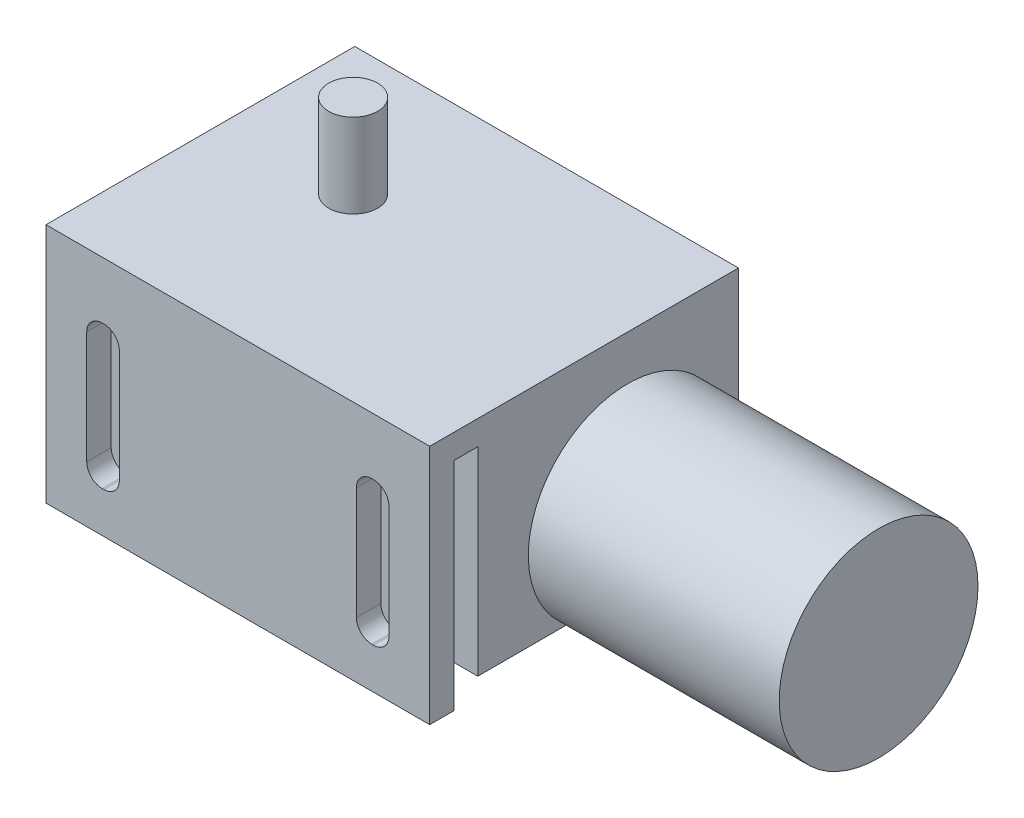
SolidWorks part; units mm, degrees
other "标注1"
sketch "草图20" plane through (-23.55, 25.1, 37.9) normal (-0.2277, 0.5156, 0.826) x (0.9602, 0.2599, 0.1025)
ref_plane "前视基准面" through (0, 0, 0) normal (0, 0, 1) x (1, 0, 0)
ref_plane "上视基准面" through (0, 0, 0) normal (0, 1, 0) x (1, 0, 0)
ref_plane "右视基准面" through (0, 0, 0) normal (1, 0, 0) x (0, 0, -1)
sketch "草图4" plane through (0, 0, 0) normal (0, 0, 1) x (1, 0, 0)
  line L1 (-23.55, 14.8) -> (23.55, 14.8)
  line L2 (-23.55, 14.8) -> (-23.55, -14.8)
  line L3 (-23.55, -14.8) -> (23.55, -14.8)
  line L4 (23.55, 14.8) -> (23.55, -14.8)
  line L5 (-23.55, 14.8) -> (23.55, -14.8) construction
  line L6 (-23.55, -14.8) -> (23.55, 14.8) construction
  point P0 (0, 0)
extrude "减速箱" add sketch "草图4" along normal blind 37.9
sketch "草图8" plane through (0, -14.8, 0) normal (0, -1, 0) x (1, 0, 0)
  line L1 (23.55, 37.9) -> (23.55, 0) construction
  line L2 (-23.55, 0) -> (23.55, 0)
  line L3 (-23.55, 0) -> (-23.55, 32)
  line L4 (-23.55, 32) -> (23.55, 32)
  line L5 (23.55, 0) -> (23.55, 32)
  dimension "D1" = 32
extrude "切除-拉伸1" cut sketch "草图8" against normal blind 2.2
sketch "草图12" plane through (0, -14.8, 0) normal (0, -1, 0) x (1, 0, 0)
  line L0 (23.55, 37.9) -> (23.55, 32) construction
  line L1 (-23.55, 32) -> (23.55, 32)
  line L2 (-23.55, 32) -> (-23.55, 34.9)
  line L3 (-23.55, 34.9) -> (23.55, 34.9)
  line L4 (23.55, 32) -> (23.55, 34.9)
  dimension "D1" = 2.9
extrude "固定凹槽" cut sketch "草图12" against normal offset from surface (26.6 mm away) 3 up to face at (0, 14.8, 18.95)
sketch "草图14" plane through (0, 0, 37.9) normal (0, 0, 1) x (1, 0, 0)
  line L0 (-23.55, 14.8) -> (-23.55, -14.8) construction
  line L3 (-23.55, -14.8) -> (23.55, -14.8) construction
  line L5 (23.55, 14.8) -> (-23.55, 14.8) construction
  line L9 (-14.55, 7.8) -> (-16.65, 7.8)
  line L10 (-14.55, 5.9) -> (-14.55, -7.9)
  line L11 (-16.45, -9.8) -> (-18.55, -9.8)
  line L12 (-18.55, 5.9) -> (-18.55, -7.9)
  arc A0 (-16.45, 7.8) -> (-14.55, 5.9) centre (-16.45, 5.9) cw
  arc A1 (-16.65, -9.8) -> (-18.55, -7.9) centre (-16.65, -7.9) cw
  arc A2 (-14.55, -7.9) -> (-16.45, -9.8) centre (-16.45, -7.9) cw
  arc A3 (-18.55, 5.9) -> (-16.65, 7.8) centre (-16.65, 5.9) cw
  point P0 (-23.55, 0)
  point P5 (0, 0)
  point P6 (-16.55, -14.8)
  point P11 (-16.55, 14.8)
  dimension "D6" = 1.9
  dimension "D1" = 7
  dimension "D2" = 5
  dimension "D3" = 5
  dimension "D4" = 4
extrude "切除-拉伸3" cut sketch "草图14" against normal up to surface (3 mm away) contours A3 L12 A1 L11 A2 L10 A0 L9 up to face at (0, -1.5, 34.9)
ref_plane "基准面7" through (0, 0, 0) normal (1, 0, 0) x (0, 0, -1)
mirror "镜向3" about plane through (0, 0, 0) normal (1, 0, 0) of "切除-拉伸3"
sketch "草图17" plane through (0, 14.8, 0) normal (0, 1, 0) x (1, 0, 0)
  line L0 (-23.55, 0) -> (-7.95, 0) construction
  line L1 (23.55, 0) -> (-23.55, 0) construction
  line L2 (-7.95, 0) -> (-7.95, -15.8) construction
  circle A0 centre (-7.95, -15.8) radius 3
  dimension "D1" = 15.6
  dimension "D2" = 15.8
extrude "传动轴" add sketch "草图17" along normal blind 10.3
sketch "草图19" plane through (23.55, 0, 0) normal (1, 0, 0) x (0, 0, -1)
  line L0 (0, -12.6) -> (0, -2.9) construction
  line L1 (0, -12.6) -> (0, 14.8) construction
  line L2 (0, -2.9) -> (-13.6, -2.9) construction
  circle A0 centre (-13.6, -2.9) radius 12.2
  dimension "D1" = 9.7
  dimension "D2" = 13.6
extrude "电机" add sketch "草图19" along normal blind 30.8
